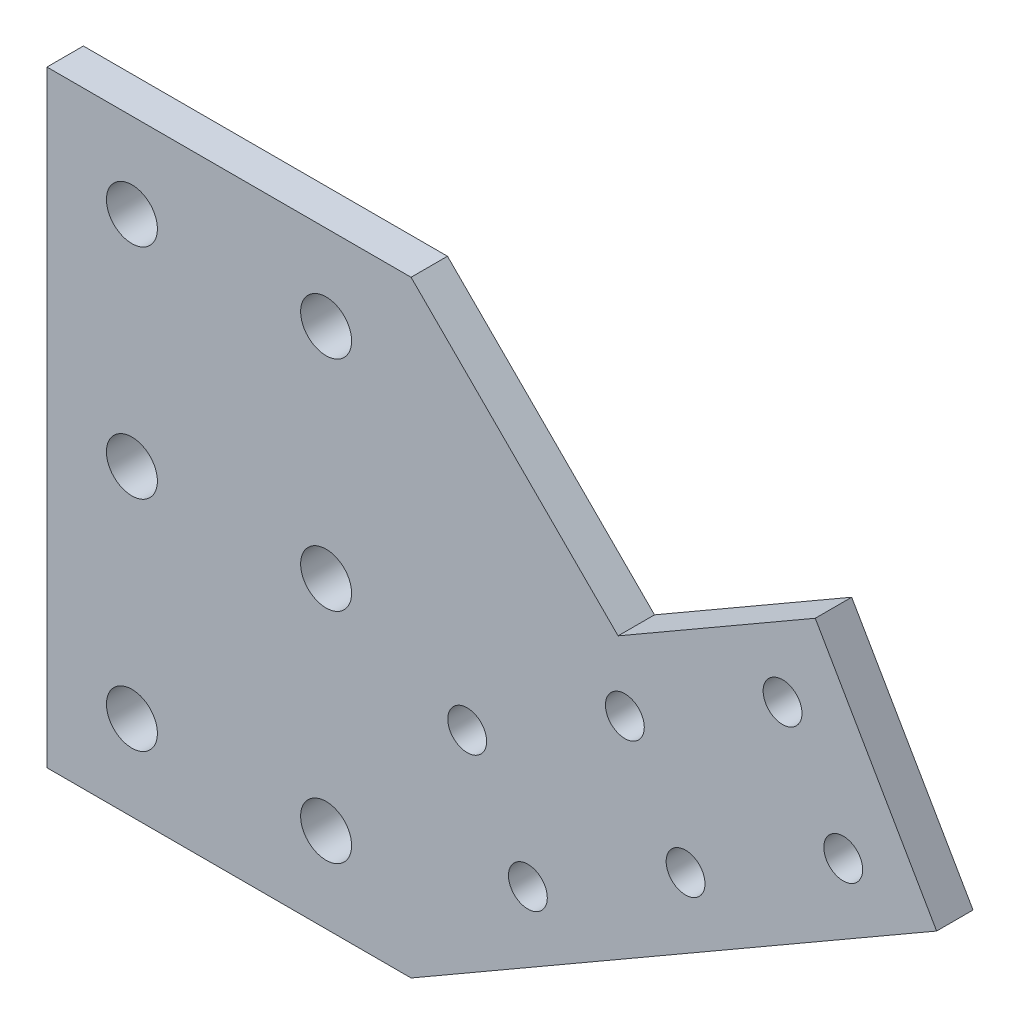
SolidWorks part; units mm, degrees
material "Thornel VCB-20 碳布"
ref_plane "前视基准面" through (0, 0, 0) normal (0, 0, 1) x (1, 0, 0)
ref_plane "上视基准面" through (0, 0, 0) normal (0, 1, 0) x (1, 0, 0)
ref_plane "右视基准面" through (0, 0, 0) normal (1, 0, 0) x (0, 0, -1)
other "Configuration Table"
sketch "草图1" plane through (0, 0, 0) normal (0, 0, 1) x (1, 0, 0)
  line L0 (0, 0) -> (0, 120) construction
  line L1 (0, 120) -> (207.8461, 120) construction
  line L2 (0, 0) -> (207.8461, 120) construction
  line L3 (0, 0) -> (-30, 0)
  line L4 (-30, 0) -> (-30, 50)
  line L5 (-30, 50) -> (0, 50)
  line L6 (0, 50) -> (17.0577, 32.9423)
  line L7 (17.0577, 32.9423) -> (33.3013, 42.3205)
  line L8 (33.3013, 42.3205) -> (43.3013, 25)
  line L9 (43.3013, 25) -> (0, 0)
  dimension "D1" = 60
  dimension "D2" = 240
  dimension "D3" = 20
  dimension "D4" = 30
  dimension "D5" = 50
  dimension "D6" = 50
  dimension "D7" = 45
extrude "凸台-拉伸1" add sketch "草图1" along normal blind 3
sketch "草图2" plane through (0, 0, 3) normal (0, 0, 1) x (1, 0, 0)
  line L0 (0, 50) -> (0, 0) construction
  line L1 (17.0577, 32.9423) -> (0, 23.094) construction
  line L2 (-30, 50) -> (-30, 0) construction
  line L3 (-23, 43) -> (-7, 43) construction
  line L4 (-23, 43) -> (-23, 7) construction
  line L5 (-23, 7) -> (-7, 7) construction
  line L6 (-7, 43) -> (-7, 7) construction
  line L7 (0, 50) -> (-30, 50) construction
  line L10 (0, 0) -> (43.3013, 25) construction
  line L11 (30.6051, 34.9904) -> (35.6051, 26.3301) construction
  line L12 (35.6051, 26.3301) -> (9.6244, 11.3301) construction
  line L13 (9.6244, 11.3301) -> (4.6244, 19.9904) construction
  line L14 (4.6244, 19.9904) -> (30.6051, 34.9904) construction
  line L15 (43.3013, 25) -> (33.3013, 42.3205) construction
  circle A0 centre (-23, 43) radius 2.1
  circle A1 centre (-7, 43) radius 2.1
  circle A2 centre (-23, 7) radius 2.1
  circle A3 centre (-7, 7) radius 2.1
  circle A4 centre (-23, 25) radius 2.1
  circle A5 centre (-7, 25) radius 2.1
  circle A6 centre (30.6051, 34.9904) radius 1.6
  circle A7 centre (35.6051, 26.3301) radius 1.6
  circle A8 centre (22.6147, 18.8301) radius 1.6
  circle A9 centre (17.6147, 27.4904) radius 1.6
  circle A10 centre (4.6244, 19.9904) radius 1.6
  circle A11 centre (9.6244, 11.3301) radius 1.6
  dimension "D5" = 4.2
  dimension "D10" = 3.2
  dimension "D1" = 16
  dimension "D2" = 7
  dimension "D3" = 36
  dimension "D4" = 7
  dimension "D6" = 10
  dimension "D7" = 5
  dimension "D8" = 30
  dimension "D9" = 6
extrude "切除-拉伸1" cut sketch "草图2" against normal through all
